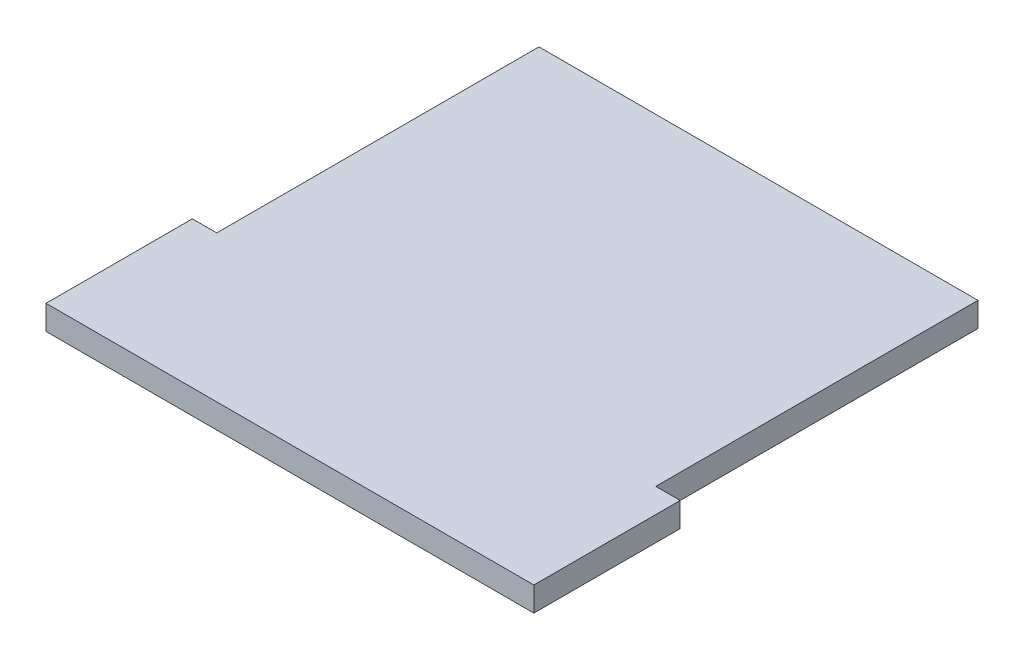
SolidWorks part; units mm, degrees
material "AISI 4130 Steel, annealed at 865C"
ref_plane "X-Y Datum" through (0, 0, 0) normal (0, 0, 1) x (1, 0, 0)
ref_plane "X-Z Datum" through (0, 0, 0) normal (0, 1, 0) x (1, 0, 0)
ref_plane "Y-Z Datum" through (0, 0, 0) normal (1, 0, 0) x (0, 0, -1)
sketch "Sketch1" plane through (0, 0, 0) normal (0, 1, 0) x (1, 0, 0)
  line L0 (15.875, 0) -> (-15.875, 0)
  line L1 (-15.875, 0) -> (-15.875, 9.525)
  line L2 (-15.875, 9.525) -> (-14.2875, 9.525)
  line L3 (-14.2875, 9.525) -> (-14.2875, 30.4939)
  line L4 (-14.2875, 30.4939) -> (14.2875, 30.4939)
  line L5 (14.2875, 30.4939) -> (14.2875, 9.525)
  line L6 (14.2875, 9.525) -> (15.875, 9.525)
  line L7 (15.875, 9.525) -> (15.875, 0)
  point P4 (0, 0)
extrude "Boss-Extrude1" add sketch "Sketch1" along normal blind 1.5875
